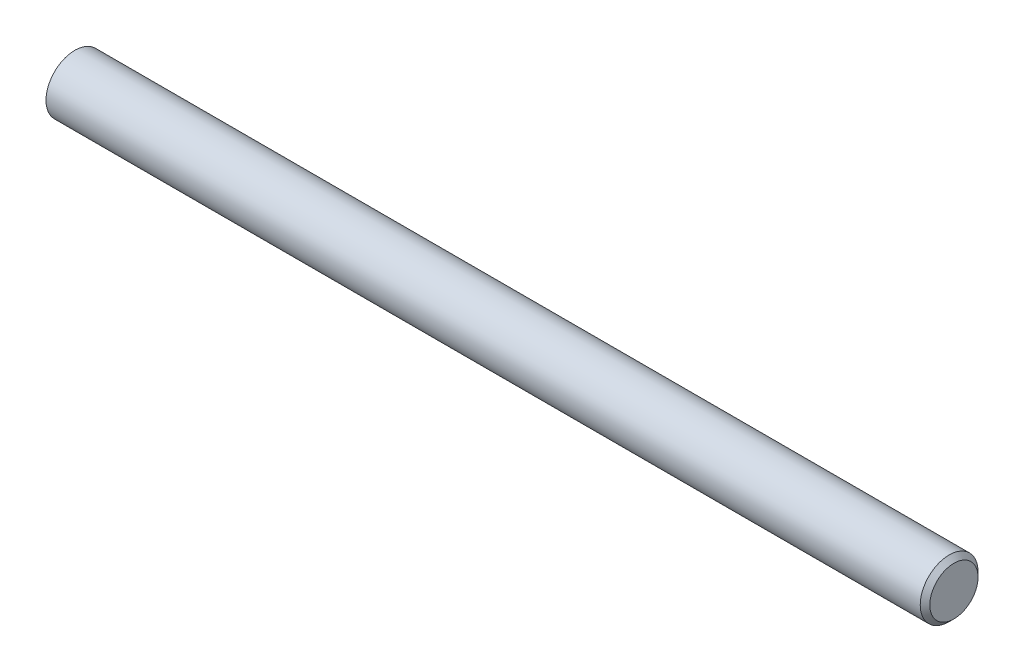
SolidWorks part; units mm, degrees
ref_plane "Plane1" through (0, 0, 0) normal (0, 0, 1) x (1, 0, 0)
ref_plane "Plane2" through (0, 0, 0) normal (0, 1, 0) x (1, 0, 0)
ref_plane "Plane3" through (0, 0, 0) normal (1, 0, 0) x (0, 0, -1)
sketch "BodySke" plane through (0, 0, 0) normal (0, 0, 1) x (1, 0, 0)
  line L0 (0, 0) -> (0, 5)
  line L3 (0, 5) -> (151.172, 5)
  line L4 (152, 4.172) -> (152, 0)
  line L5 (152, 0) -> (0, 0)
  line L6 (-31.75, 0) -> (127, 0) construction
  line L8 (152, 4.172) -> (151.172, 5)
  line L10 (152, -4.172) -> (151.172, -5) construction
  line L11 (1.5, 4.525) -> (1.5, -1.825) construction
  line L12 (107, 4.525) -> (107, -1.825) construction
  line L13 (92, 4.525) -> (92, -1.825) construction
  dimension "Body_ch_ang" = 45
  dimension "Diameter" = 10
  dimension "Minor_dia" = 8.344
  dimension "Advance" = 1.5
  dimension "Thread_nom" = 45
  dimension "Thread_length" = 60
  dimension "Length" = 152
revolve "Base-Revolve" add sketch "BodySke" angle 360 about L6
cosmetic thread "ThreadCosmetic" [suppressed] parameters "Thread_length"=45, "Thread_minor"=8.344
sketch "ThdSchSke" plane through (0, 0, 0) normal (0, 0, 1) x (1, 0, 0)
  line L0 (107, -4.172) -> (106.4202, -5)
  line L1 (107, -4.172) -> (107.5798, -5)
  line L2 (107.5798, -5) -> (107.5798, -6.25)
  line L3 (-3.175, 0) -> (5.1513, 0) construction
  line L5 (107.5798, -6.25) -> (106.4202, -6.25)
  line L6 (106.4202, -6.25) -> (106.4202, -5)
  dimension "Thread_minor" = 8.344
  dimension "Diameter" = 10
  dimension "SideAngle" = 55
  dimension "VeeAngle" = 70
  dimension "Overcut" = 12.5
  dimension "Start" = 107
revolve "ThreadSchematic" [suppressed] cut sketch "ThdSchSke" angle 360 about L3
pattern_linear "ThdSchPat" [suppressed]
equation "\"Thread_minor@ThreadCosmetic\"  =  \"Minor_dia@BodySke\""
equation "\"Thread_length@ThreadCosmetic\" = ((sgn( (\"Length@BodySke\" - \"Advance@BodySke\" * 3.0) - \"Thread_nom@BodySke\" )-1)*( (\"Length@BodySke\" - \"Advance@BodySke\" * 3.0) - \"Thread_nom@BodySke\" ))/-2+ \"Thread_nom@BodySke\""
equation "\"Thread_minor@ThdSchSke\" = \"Minor_dia@BodySke\""
equation "\"Diameter@ThdSchSke\" = \"Diameter@BodySke\""
equation "\"Overcut@ThdSchSke\" = \"Diameter@BodySke\" * 1.25"
equation "\"Start@ThdSchSke\" =  \"Length@BodySke\" - \"Thread_length@ThreadCosmetic\"    '---Non-countersunk---"
equation "\"Num_threads@ThdSchPat\" = int( \"Thread_length@ThreadCosmetic\" / \"Advance@BodySke\" + 0.999 )  + 1"
equation "\"Advance@ThdSchPat\" = \"Thread_length@ThreadCosmetic\" /  (\"Num_threads@ThdSchPat\" - 1) 'relax it"
equation "\"Num_threads@ThdSchPat\" = \"Num_threads@ThdSchPat\" - sgn( \"Num_threads@ThdSchPat\" - 1) '---chamfered tips only---"
